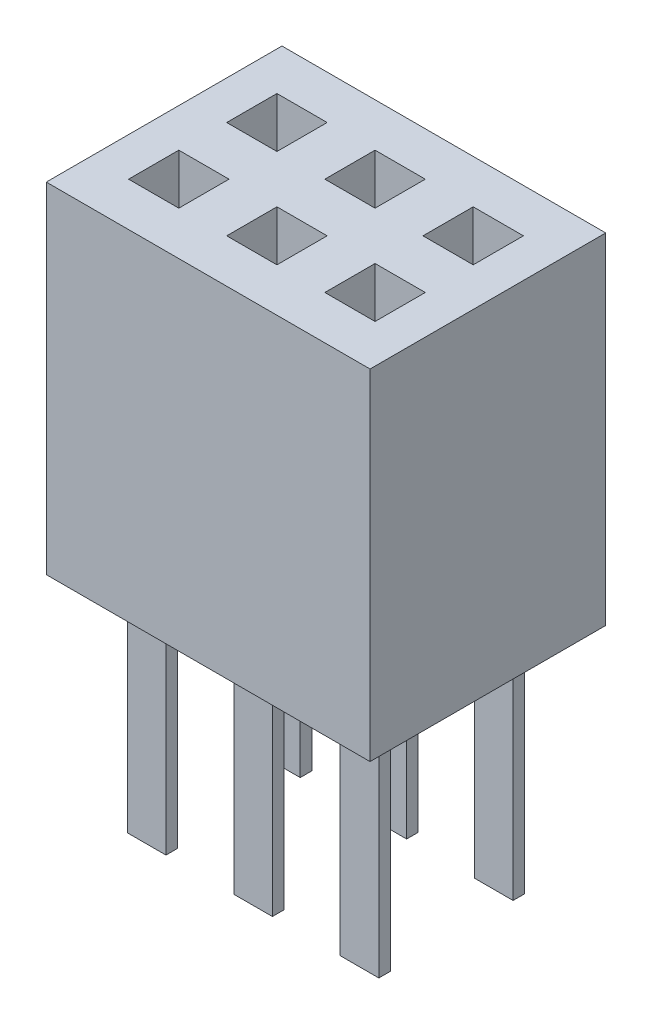
SolidWorks part; units mm, degrees
ref_plane "Plan de face" through (0, 0, 0) normal (0, 0, 1) x (1, 0, 0)
ref_plane "Plan de dessus" through (0, 0, 0) normal (0, 1, 0) x (1, 0, 0)
ref_plane "Plan de droite" through (0, 0, 0) normal (1, 0, 0) x (0, 0, -1)
sketch "Esquisse2" plane through (0, 0, 0) normal (0, 1, 0) x (1, 0, 0)
  line L1 (-2.095, -1.525) -> (2.095, -1.525)
  line L2 (-2.095, -1.525) -> (-2.095, 1.525)
  line L3 (-2.095, 1.525) -> (2.095, 1.525)
  line L4 (2.095, -1.525) -> (2.095, 1.525)
  line L5 (-2.095, -1.525) -> (2.095, 1.525) construction
  line L6 (-2.095, 1.525) -> (2.095, -1.525) construction
  point P0 (0, 0)
  dimension "D1" = 3.05
  dimension "D2" = 4.19
extrude "Boss.-Extru.1" add sketch "Esquisse2" along normal blind 4.4
sketch "Esquisse4" plane through (0, 4.4, 0) normal (0, 1, 0) x (1, 0, 0)
  line L0 (0, 0.635) -> (0, -0.635) construction
  line L1 (-1.27, -0.635) -> (1.27, -0.635) construction
  line L2 (-1.27, -0.635) -> (-1.27, 0.635) construction
  line L3 (-1.27, 0.635) -> (1.27, 0.635) construction
  line L4 (1.27, -0.635) -> (1.27, 0.635) construction
  line L5 (-1.27, -0.635) -> (1.27, 0.635) construction
  line L6 (-1.27, 0.635) -> (1.27, -0.635) construction
  line L8 (-1.595, 0.31) -> (-0.945, 0.31)
  line L9 (-1.595, 0.31) -> (-1.595, 0.96)
  line L10 (-1.595, 0.96) -> (-0.945, 0.96)
  line L11 (-0.945, 0.31) -> (-0.945, 0.96)
  line L12 (-1.595, 0.31) -> (-0.945, 0.96) construction
  line L13 (-1.595, 0.96) -> (-0.945, 0.31) construction
  line L14 (-0.325, 0.31) -> (0.325, 0.31)
  line L15 (-0.325, 0.31) -> (-0.325, 0.96)
  line L16 (-0.325, 0.96) -> (0.325, 0.96)
  line L17 (0.325, 0.31) -> (0.325, 0.96)
  line L18 (-0.325, 0.31) -> (0.325, 0.96) construction
  line L19 (-0.325, 0.96) -> (0.325, 0.31) construction
  line L20 (0.945, 0.31) -> (1.595, 0.31)
  line L21 (0.945, 0.31) -> (0.945, 0.96)
  line L22 (0.945, 0.96) -> (1.595, 0.96)
  line L23 (1.595, 0.31) -> (1.595, 0.96)
  line L24 (0.945, 0.31) -> (1.595, 0.96) construction
  line L25 (0.945, 0.96) -> (1.595, 0.31) construction
  line L26 (-1.595, -0.96) -> (-0.945, -0.96)
  line L27 (-1.595, -0.96) -> (-1.595, -0.31)
  line L28 (-1.595, -0.31) -> (-0.945, -0.31)
  line L29 (-0.945, -0.96) -> (-0.945, -0.31)
  line L30 (-1.595, -0.96) -> (-0.945, -0.31) construction
  line L31 (-1.595, -0.31) -> (-0.945, -0.96) construction
  line L32 (-0.325, -0.96) -> (0.325, -0.96)
  line L33 (-0.325, -0.96) -> (-0.325, -0.31)
  line L34 (-0.325, -0.31) -> (0.325, -0.31)
  line L35 (0.325, -0.96) -> (0.325, -0.31)
  line L36 (-0.325, -0.96) -> (0.325, -0.31) construction
  line L37 (-0.325, -0.31) -> (0.325, -0.96) construction
  line L38 (0.945, -0.96) -> (1.595, -0.96)
  line L39 (0.945, -0.96) -> (0.945, -0.31)
  line L40 (0.945, -0.31) -> (1.595, -0.31)
  line L41 (1.595, -0.96) -> (1.595, -0.31)
  line L42 (0.945, -0.96) -> (1.595, -0.31) construction
  line L43 (0.945, -0.31) -> (1.595, -0.96) construction
  point P0 (0, 0)
  dimension "D1" = 2.54
  dimension "D2" = 1.27
  dimension "D3" = 0.65
extrude "Enlèv. mat.-Extru.1" cut sketch "Esquisse4" against normal blind 3.5
sketch "Esquisse5" plane through (0, 0, 0) normal (0, -1, 0) x (1, 0, 0)
  line L0 (0, 0.8687) -> (0, -0.8687) construction
  line L1 (-1.3774, -0.8687) -> (1.3774, -0.8687) construction
  line L2 (-1.3774, -0.8687) -> (-1.3774, 0.8687) construction
  line L3 (-1.3774, 0.8687) -> (1.3774, 0.8687) construction
  line L4 (1.3774, -0.8687) -> (1.3774, 0.8687) construction
  line L5 (-1.3774, -0.8687) -> (1.3774, 0.8687) construction
  line L6 (-1.3774, 0.8687) -> (1.3774, -0.8687) construction
  line L8 (-1.6274, 0.7937) -> (-1.1274, 0.7937)
  line L9 (-1.6274, 0.7937) -> (-1.6274, 0.9437)
  line L10 (-1.6274, 0.9437) -> (-1.1274, 0.9437)
  line L11 (-1.1274, 0.7937) -> (-1.1274, 0.9437)
  line L12 (-1.6274, 0.7937) -> (-1.1274, 0.9437) construction
  line L13 (-1.6274, 0.9437) -> (-1.1274, 0.7937) construction
  line L14 (-0.25, 0.7937) -> (0.25, 0.7937)
  line L15 (-0.25, 0.7937) -> (-0.25, 0.9437)
  line L16 (-0.25, 0.9437) -> (0.25, 0.9437)
  line L17 (0.25, 0.7937) -> (0.25, 0.9437)
  line L18 (-0.25, 0.7937) -> (0.25, 0.9437) construction
  line L19 (-0.25, 0.9437) -> (0.25, 0.7937) construction
  line L20 (1.1274, 0.7937) -> (1.6274, 0.7937)
  line L21 (1.1274, 0.7937) -> (1.1274, 0.9437)
  line L22 (1.1274, 0.9437) -> (1.6274, 0.9437)
  line L23 (1.6274, 0.7937) -> (1.6274, 0.9437)
  line L24 (1.1274, 0.7937) -> (1.6274, 0.9437) construction
  line L25 (1.1274, 0.9437) -> (1.6274, 0.7937) construction
  line L26 (-1.6274, -0.9437) -> (-1.1274, -0.9437)
  line L27 (-1.6274, -0.9437) -> (-1.6274, -0.7937)
  line L28 (-1.6274, -0.7937) -> (-1.1274, -0.7937)
  line L29 (-1.1274, -0.9437) -> (-1.1274, -0.7937)
  line L30 (-1.6274, -0.9437) -> (-1.1274, -0.7937) construction
  line L31 (-1.6274, -0.7937) -> (-1.1274, -0.9437) construction
  line L32 (-0.25, -0.9437) -> (0.25, -0.9437)
  line L33 (-0.25, -0.9437) -> (-0.25, -0.7937)
  line L34 (-0.25, -0.7937) -> (0.25, -0.7937)
  line L35 (0.25, -0.9437) -> (0.25, -0.7937)
  line L36 (-0.25, -0.9437) -> (0.25, -0.7937) construction
  line L37 (-0.25, -0.7937) -> (0.25, -0.9437) construction
  line L38 (1.1274, -0.9437) -> (1.6274, -0.9437)
  line L39 (1.1274, -0.9437) -> (1.1274, -0.7937)
  line L40 (1.1274, -0.7937) -> (1.6274, -0.7937)
  line L41 (1.6274, -0.9437) -> (1.6274, -0.7937)
  line L42 (1.1274, -0.9437) -> (1.6274, -0.7937) construction
  line L43 (1.1274, -0.7937) -> (1.6274, -0.9437) construction
  point P0 (0, 0)
  dimension "D1" = 0.15
  dimension "D2" = 0.5
extrude "Boss.-Extru.2" add sketch "Esquisse5" along normal blind 3
chamfer "Chanfrein1" distance 0.05 angle 45 24 edges at (-1.3774, -3, -0.9437) (-1.6274, -3, -0.8687) (-1.3774, -3, -0.7937) (-1.1274, -3, -0.8687) (0, -3, -0.9437) (-0.25, -3, -0.8687) (0, -3, -0.7937) (0.25, -3, -0.8687) (1.3774, -3, -0.9437) (1.1274, -3, -0.8687) (1.3774, -3, -0.7937) (1.6274, -3, -0.8687) (1.3774, -3, 0.7937) (1.1274, -3, 0.8687) (1.3774, -3, 0.9437) (1.6274, -3, 0.8687) (0, -3, 0.7937) (-0.25, -3, 0.8687) (0, -3, 0.9437) (0.25, -3, 0.8687) (-1.3774, -3, 0.7937) (-1.6274, -3, 0.8687) (-1.3774, -3, 0.9437) (-1.1274, -3, 0.8687)
